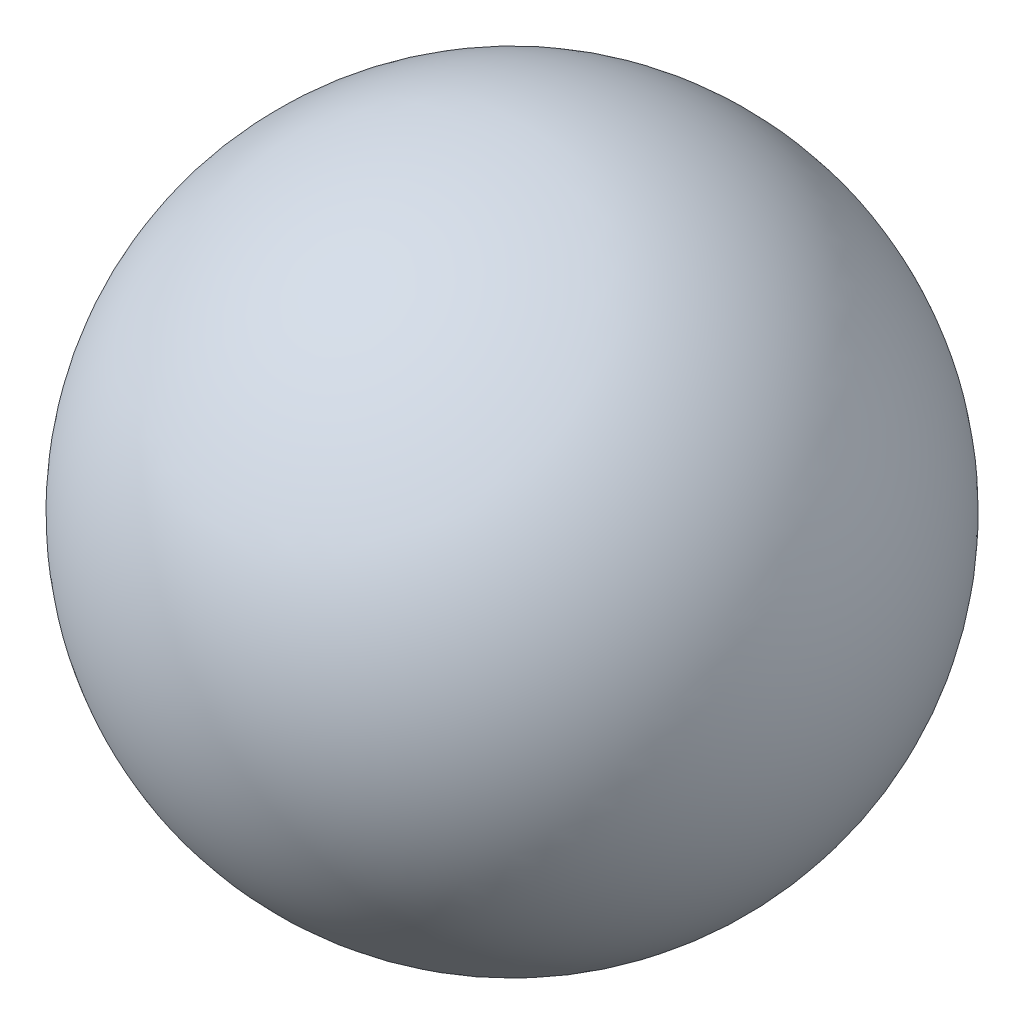
SolidWorks part; units mm, degrees
material "1.4000 (X6Cr13)"
ref_plane "前视基准面" through (0, 0, 0) normal (0, 0, 1) x (1, 0, 0)
ref_plane "上视基准面" through (0, 0, 0) normal (0, 1, 0) x (1, 0, 0)
ref_plane "右视基准面" through (0, 0, 0) normal (1, 0, 0) x (0, 0, -1)
sketch "草图1" plane through (0, 0, 0) normal (0, 1, 0) x (1, 0, 0)
  line L0 (0, -1.325) -> (0, 1.325)
  arc A0 (0, -1.325) -> (0, 1.325) centre (0, 0) ccw
  dimension "D1" = 2.65
revolve "旋转1" add sketch "草图1" angle 360 about L0
